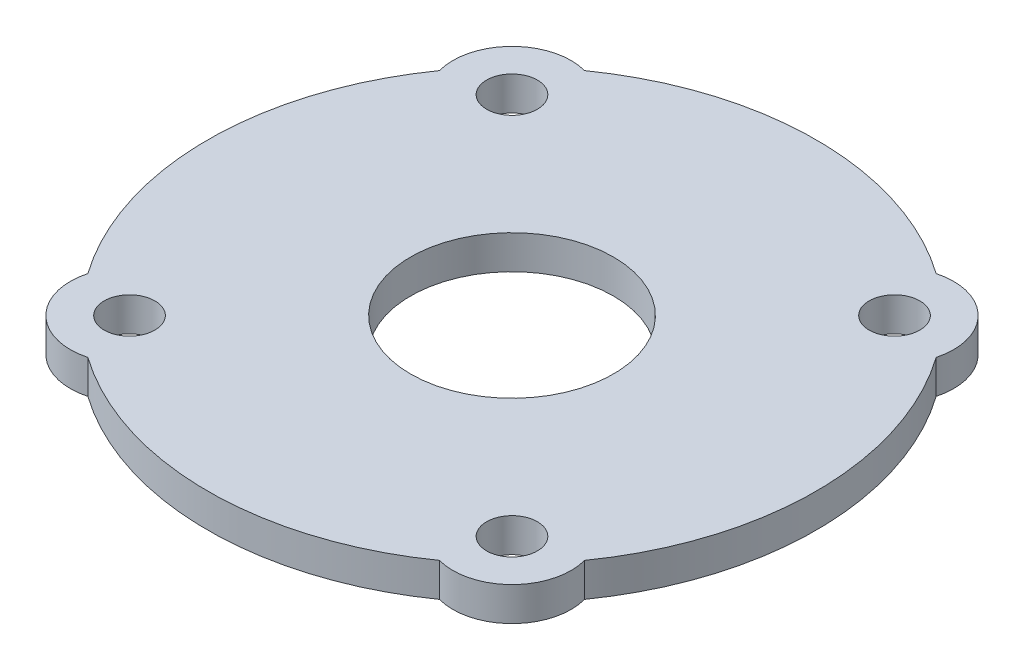
SolidWorks part; units mm, degrees
ref_plane "Front Plane" through (0, 0, 0) normal (0, 0, 1) x (1, 0, 0)
ref_plane "Top Plane" through (0, 0, 0) normal (0, 1, 0) x (1, 0, 0)
ref_plane "Right Plane" through (0, 0, 0) normal (1, 0, 0) x (0, 0, -1)
sketch "Sketch1" plane through (0, 0, 0) normal (0, 1, 0) x (1, 0, 0)
  line L0 (-17.9605, 17.9605) -> (0, 0) construction
  line L5 (0, -19.05) -> (0, 19.05) construction
  line L6 (-19.05, 0) -> (19.05, 0) construction
  arc A0 (-16.1996, 19.5635) -> (-9.784, 23.44) centre (0, 0) ccw construction
  circle A1 centre (-17.9605, 17.9605) radius 2.3813
  circle A2 centre (17.9605, 17.9605) radius 2.3813
  circle A3 centre (-17.9605, -17.9605) radius 2.3813
  circle A4 centre (17.9605, -17.9605) radius 2.3813
  arc A5 (-16.5086, 23.3237) -> (-23.3237, 16.5086) centre (-17.9605, 17.9605) ccw
  arc A6 (16.5086, 23.3237) -> (23.3237, 16.5086) centre (17.9605, 17.9605) cw
  arc A7 (-16.5086, -23.3237) -> (-23.3237, -16.5086) centre (-17.9605, -17.9605) cw
  arc A8 (16.5086, -23.3237) -> (23.3237, -16.5086) centre (17.9605, -17.9605) ccw
  arc A9 (-23.3237, 16.5086) -> (-23.3237, -16.5086) centre (0, 0) ccw
  circle A10 centre (-17.9605, 17.9605) radius 5.5562 construction
  circle A11 centre (0, 0) radius 25.4 construction
  circle A12 centre (0, 0) radius 28.575 construction
  circle A13 centre (17.9605, 17.9605) radius 5.5562 construction
  arc A14 (16.5086, 23.3237) -> (-16.5086, 23.3237) centre (0, 0) ccw
  circle A15 centre (17.9605, -17.9605) radius 5.5562 construction
  arc A16 (23.3237, -16.5086) -> (23.3237, 16.5086) centre (0, 0) ccw
  circle A17 centre (-17.9605, -17.9605) radius 5.5562 construction
  arc A18 (-16.5086, -23.3237) -> (16.5086, -23.3237) centre (0, 0) ccw
  circle A19 centre (0, 0) radius 9.525
  point P0 (0, 0)
  dimension "D1" = 25.4
  dimension "D3" = 4.7625
  dimension "D5" = 19.05
  dimension "D2" = 3.175
  dimension "D4" = 45
extrude "Boss-Extrude1" add sketch "Sketch1" along normal mid plane 3.175
